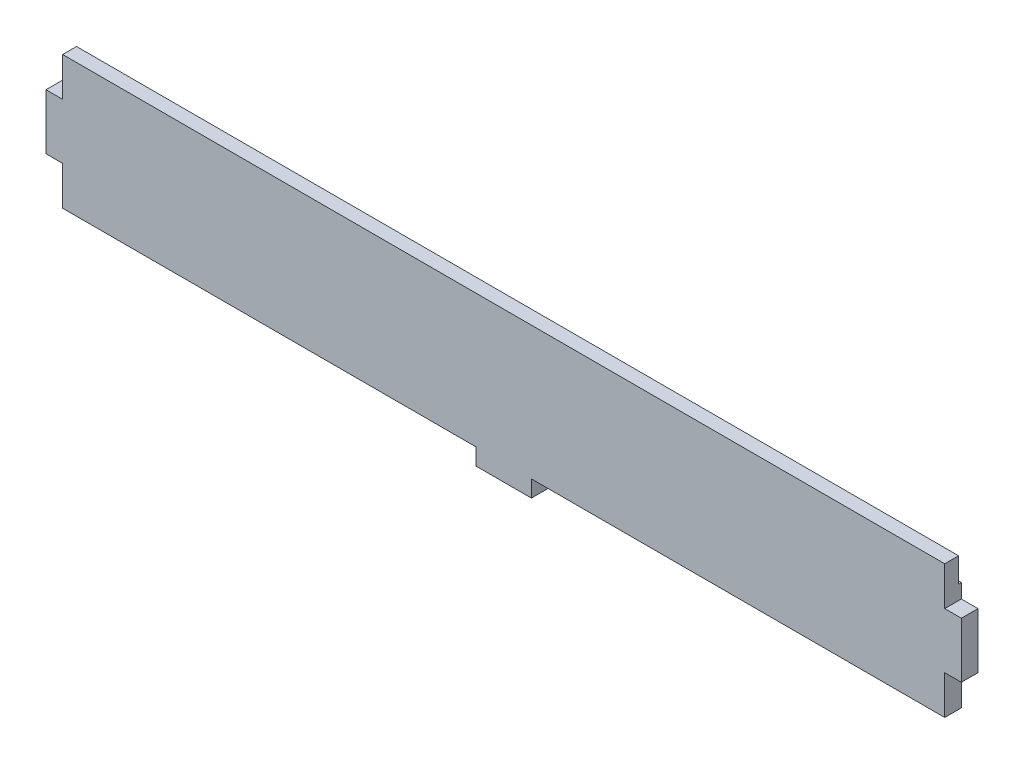
SolidWorks part; units mm, degrees
ref_plane "Plan de face" through (0, 0, 0) normal (0, 0, 1) x (1, 0, 0)
ref_plane "Plan de dessus" through (0, 0, 0) normal (0, 1, 0) x (1, 0, 0)
ref_plane "Plan de droite" through (0, 0, 0) normal (1, 0, 0) x (0, 0, -1)
sketch "Esquisse1" plane through (0, 0, 0) normal (0, 0, 1) x (1, 0, 0)
  line L1 (0, 0) -> (-330, 0)
  line L2 (0, 0) -> (0, 54)
  line L3 (0, 54) -> (-330, 54)
  line L4 (-330, 0) -> (-330, 54)
  dimension "D1" = 330
  dimension "D2" = 54
extrude "Boss.-Extru.1" add sketch "Esquisse1" along normal blind 6
sketch "Esquisse2" plane through (0, 0, 6) normal (0, 0, 1) x (1, 0, 0)
  line L0 (-330, 54) -> (-330, 0) construction
  line L1 (-330, 0) -> (-175, 0)
  line L2 (-330, 0) -> (-330, 20)
  line L3 (-330, 20) -> (-324, 20)
  line L4 (-324, 6) -> (-324, 20)
  line L5 (-330, 0) -> (0, 0) construction
  line L7 (-324, 40) -> (-324, 54)
  line L8 (-330, 54) -> (-330, 40)
  line L9 (-330, 40) -> (-324, 40)
  line L10 (0, 54) -> (-330, 54) construction
  line L11 (-155, 0) -> (0, 0)
  line L12 (-324, 54) -> (-330, 54)
  line L13 (-324, 6) -> (-175, 6)
  line L14 (-175, 0) -> (-175, 6)
  line L15 (-6, 40) -> (-6, 54)
  line L16 (0, 0) -> (0, 20)
  line L17 (0, 20) -> (-6, 20)
  line L18 (-6, 6) -> (-6, 20)
  line L19 (-6, 54) -> (0, 54)
  line L20 (0, 54) -> (0, 40)
  line L21 (0, 40) -> (-6, 40)
  line L24 (-155, 0) -> (-155, 6)
  line L25 (-155, 6) -> (-6, 6)
  dimension "D1" = 6
  dimension "D2" = 6
  dimension "D3" = 20
  dimension "D4" = 6
  dimension "D6" = 6
  dimension "D7" = 6
  dimension "D8" = 6
  dimension "D9" = 20
  dimension "D10" = 20
  dimension "D12" = 20
  dimension "D14" = 155
  dimension "D15" = 20
extrude "Enlèv. mat.-Extru.1" cut sketch "Esquisse2" against normal through all
sketch "Esquisse4" plane through (0, 0, 0) normal (0, 0, -1) x (-1, 0, 0)
  line L0 (324, 40) -> (324, 54) construction
  line L1 (6, 54) -> (324, 54)
  line L2 (6, 54) -> (6, 45.1296)
  line L3 (6, 45.1296) -> (324, 45.1296)
  line L4 (324, 54) -> (324, 45.1296)
extrude "Enlèv. mat.-Extru.2" cut sketch "Esquisse4" against normal blind 1
